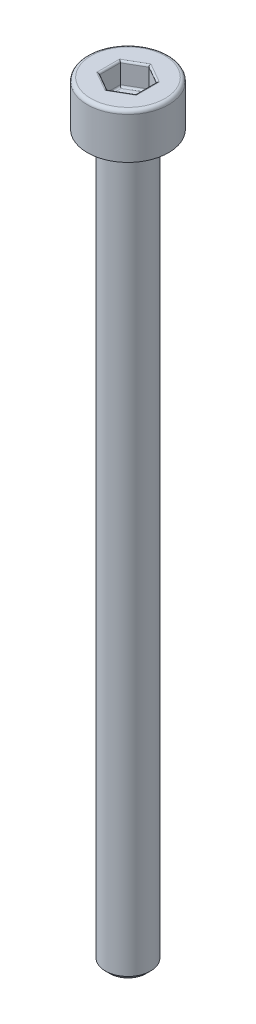
SolidWorks part; units mm, degrees
ref_plane "Front Plane" through (0, 0, 0) normal (0, 0, 1) x (1, 0, 0)
ref_plane "Top Plane" through (0, 0, 0) normal (0, 1, 0) x (1, 0, 0)
ref_plane "Right Plane" through (0, 0, 0) normal (1, 0, 0) x (0, 0, -1)
sketch "Sketch1" plane through (0, 0, 0) normal (0, 0, 1) x (1, 0, 0)
  line L0 (0, 0) -> (0, -47.0967) construction
  line L1 (0, -42.5) -> (-1.25, -42.5)
  line L2 (-1.25, -42.5) -> (-1.25, -2.5)
  line L3 (-1.25, -2.5) -> (-2.25, -2.5)
  line L4 (-2.25, -2.5) -> (-2.25, 0)
  line L5 (-2.25, 0) -> (0, 0)
  line L6 (0, 0) -> (0, -42.5)
  dimension "D1" = 40
  dimension "d" = 2.5
  dimension "k" = 2.5
  dimension "dk" = 4.5
revolve "Revolve1" add sketch "Sketch1" angle 360 about L0
chamfer "Chamfer1" distance 0.25 angle 45 2 edges at (0, -2.5, 1.25) (0, -42.5, 1.25)
fillet "Fillet1" radius 0.2 1 edges at (0, 0, 2.25)
sketch "Sketch2" plane through (0, 0, 0) normal (0, 1, 0) x (1, 0, 0)
  line L1 (0, 1.1547) -> (-1, 0.5774)
  line L2 (-1, 0.5774) -> (-1, -0.5774)
  line L3 (-1, -0.5774) -> (0, -1.1547)
  line L4 (0, -1.1547) -> (1, -0.5774)
  line L5 (1, -0.5774) -> (1, 0.5774)
  line L6 (1, 0.5774) -> (0, 1.1547)
  circle A0 centre (0, 0) radius 1 construction
  dimension "s" = 2
extrude "Cut-Extrude1" cut sketch "Sketch2" against normal blind 1.25
fillet "Fillet2" radius 0.1 12 edges at (-0.5, 0, -0.866) (-1, 0, 0) (-0.5, 0, 0.866) (0.5, 0, 0.866) (1, 0, 0) (0.5, 0, -0.866) (1, -1.25, 0) (0.5, -1.25, 0.866) (-0.5, -1.25, 0.866) (-1, -1.25, 0) (-0.5, -1.25, -0.866) (0.5, -1.25, -0.866)
